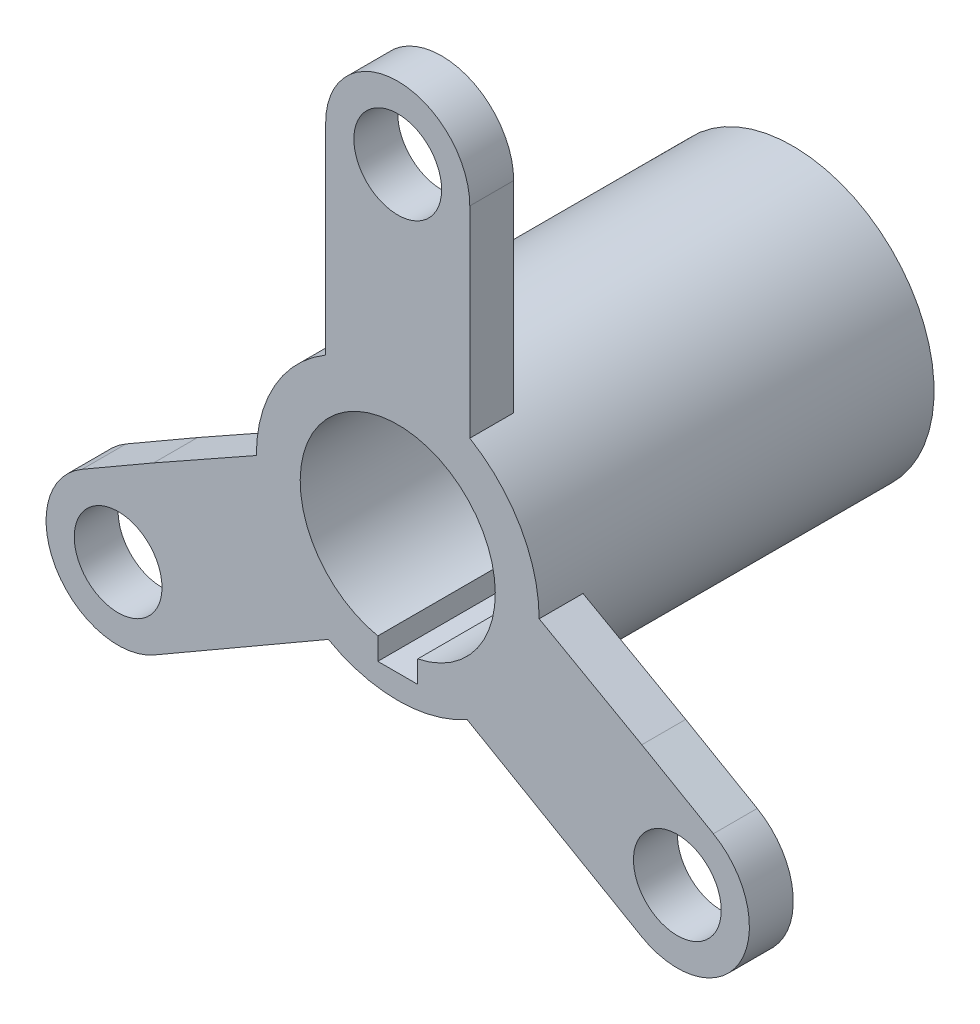
SolidWorks part; units mm, degrees
ref_plane "Płaszczyzna przednia" through (0, 0, 0) normal (0, 0, 1) x (1, 0, 0)
ref_plane "Płaszczyzna górna" through (0, 0, 0) normal (0, 1, 0) x (1, 0, 0)
ref_plane "Płaszczyzna prawa" through (0, 0, 0) normal (1, 0, 0) x (0, 0, -1)
sketch "Szkic1" plane through (0, 0, 0) normal (0, 0, 1) x (1, 0, 0)
  line L0 (35.9661, -11.2849) -> (27.8128, -6.5776)
  line L1 (-8.21, 36.79) -> (-8.21, 27.3754)
  line L2 (8.21, 36.79) -> (8.21, 27.3754)
  line L3 (27.7561, -25.5051) -> (19.6028, -20.7978)
  line L4 (-27.7561, -25.5051) -> (-19.6028, -20.7978)
  line L5 (-35.9661, -11.2849) -> (-27.8128, -6.5776)
  arc A0 (-8.21, 27.3754) -> (-27.8128, -6.5776) centre (0, 0) ccw
  arc A1 (-19.6028, -20.7978) -> (19.6028, -20.7978) centre (0, 0) ccw
  arc A2 (8.21, 36.79) -> (-8.21, 36.79) centre (0, 36.79) ccw
  circle A3 centre (0, 36.79) radius 5
  arc A4 (27.7561, -25.5051) -> (35.9661, -11.2849) centre (31.8611, -18.395) ccw
  circle A5 centre (31.8611, -18.395) radius 5
  arc A6 (-35.9661, -11.2849) -> (-27.7561, -25.5051) centre (-31.8611, -18.395) ccw
  circle A7 centre (-31.8611, -18.395) radius 5
  arc A8 (27.8128, -6.5776) -> (8.21, 27.3754) centre (0, 0) ccw
  circle A9 centre (0, 0) radius 11.115
  point P24 (0, 0)
  dimension "D1" = 22.23
  dimension "D2" = 57.16
  dimension "D3" = 10
  dimension "D4" = 3
extrude "Dodanie-wyciągnięcie1" add sketch "Szkic1" along normal blind 5
sketch "Szkic2" plane through (0, 0, 0) normal (0, 0, -1) x (-1, 0, 0)
  circle A0 centre (0, 0) radius 11.115
  circle A1 centre (0, 0) radius 16.115
  dimension "D1" = 5
extrude "Dodanie-wyciągnięcie2" add sketch "Szkic2" along normal blind 40
sketch "Szkic3" plane through (0, 0, 5) normal (0, 0, 1) x (1, 0, 0)
  line L0 (2.27, -10.8807) -> (2.27, -7.5986)
  line L1 (-2.27, -13.39) -> (2.27, -13.39)
  line L2 (2.27, -13.39) -> (2.27, -10.8807)
  line L3 (-2.27, -13.39) -> (-2.27, -10.8807)
  line L4 (2.27, -7.5986) -> (-2.27, -7.5986)
  line L5 (-2.27, -7.5986) -> (-2.27, -10.8807)
  circle A0 centre (0, 0) radius 11.115 construction
extrude "Wytnij-wyciągnięcie1" cut sketch "Szkic3" against normal through all
sketch "Szkic4" plane through (0, 0, 0) normal (0, 0, -1) x (-1, 0, 0)
  line L0 (19.6028, -20.7978) -> (7.904, -14.0435)
  line L1 (27.8128, -6.5776) -> (16.115, 0)
  line L2 (8.21, 27.3754) -> (8.21, 13.8668)
  line L3 (-8.21, 27.3754) -> (-8.21, 13.8668)
  line L4 (-19.6028, -20.7978) -> (-7.904, -14.0435)
  line L5 (-27.8128, -6.5776) -> (-16.115, 0)
  circle A0 centre (0, 0) radius 16.115 construction
  arc A1 (16.115, 0) -> (8.21, 13.8668) centre (0, 0) ccw
  arc A2 (27.8128, -6.5776) -> (8.21, 27.3754) centre (0, 0) ccw
  arc A3 (-19.6028, -20.7978) -> (19.6028, -20.7978) centre (0, 0) ccw
  arc A4 (-7.904, -14.0435) -> (7.904, -14.0435) centre (0, 0) ccw
  arc A5 (-8.21, 13.8668) -> (-16.115, 0) centre (0, 0) ccw
  arc A6 (-8.21, 27.3754) -> (-27.8128, -6.5776) centre (0, 0) ccw
extrude "Wytnij-wyciągnięcie2" cut sketch "Szkic4" against normal through all
